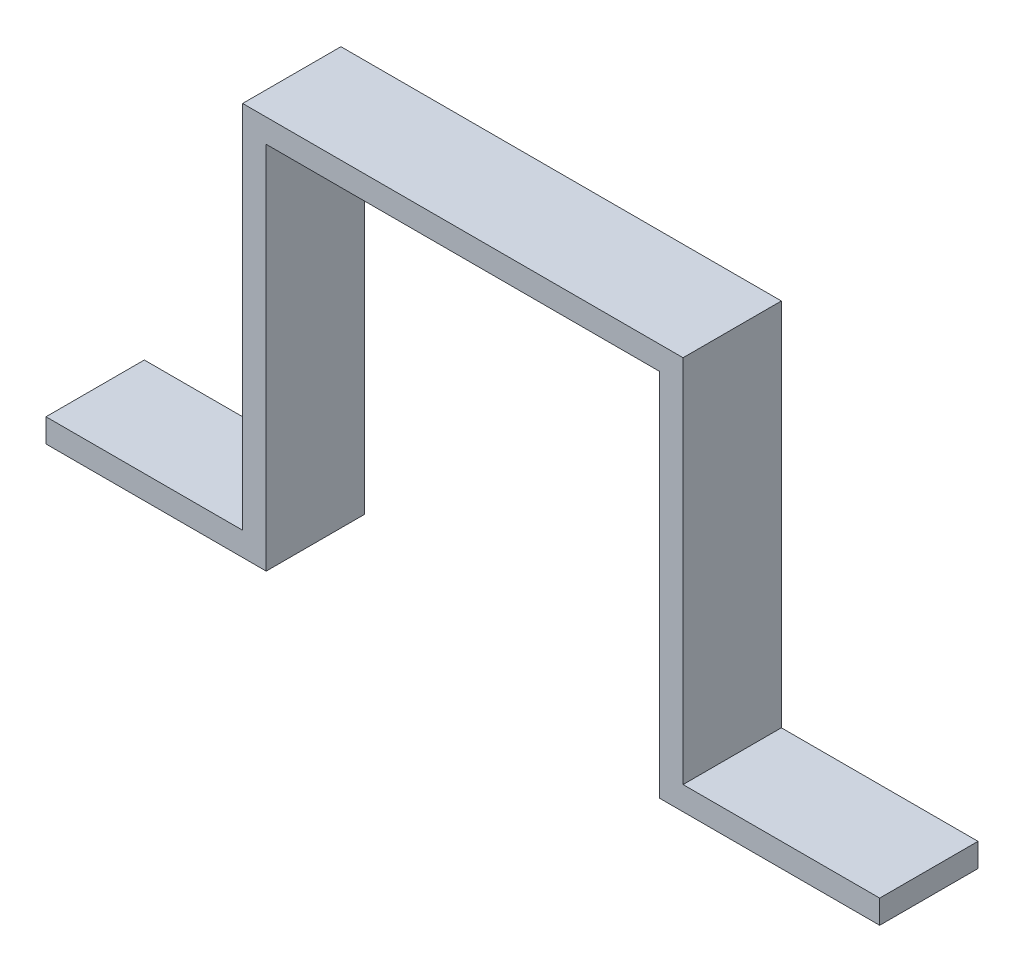
SolidWorks part; units mm, degrees
material "Plain Carbon Steel"
ref_plane "Front Plane" through (0, 0, 0) normal (0, 0, 1) x (1, 0, 0)
ref_plane "Top Plane" through (0, 0, 0) normal (0, 1, 0) x (1, 0, 0)
ref_plane "Right Plane" through (0, 0, 0) normal (1, 0, 0) x (0, 0, -1)
sketch "Sketch1" plane through (0, 0, 0) normal (0, 0, 1) x (1, 0, 0)
  line L0 (-106, 0) -> (-106, 6)
  line L1 (-106, 6) -> (-56, 6)
  line L2 (-56, 6) -> (-56, 100)
  line L3 (-56, 100) -> (56, 100)
  line L4 (56, 100) -> (56, 6)
  line L5 (56, 6) -> (106, 6)
  line L6 (106, 6) -> (106, 0)
  line L7 (106, 0) -> (50, 0)
  line L8 (50, 0) -> (50, 94)
  line L9 (50, 94) -> (-50, 94)
  line L10 (-50, 94) -> (-50, 0)
  line L11 (-50, 0) -> (-106, 0)
extrude "Boss-Extrude1" add sketch "Sketch1" along normal mid plane 25
